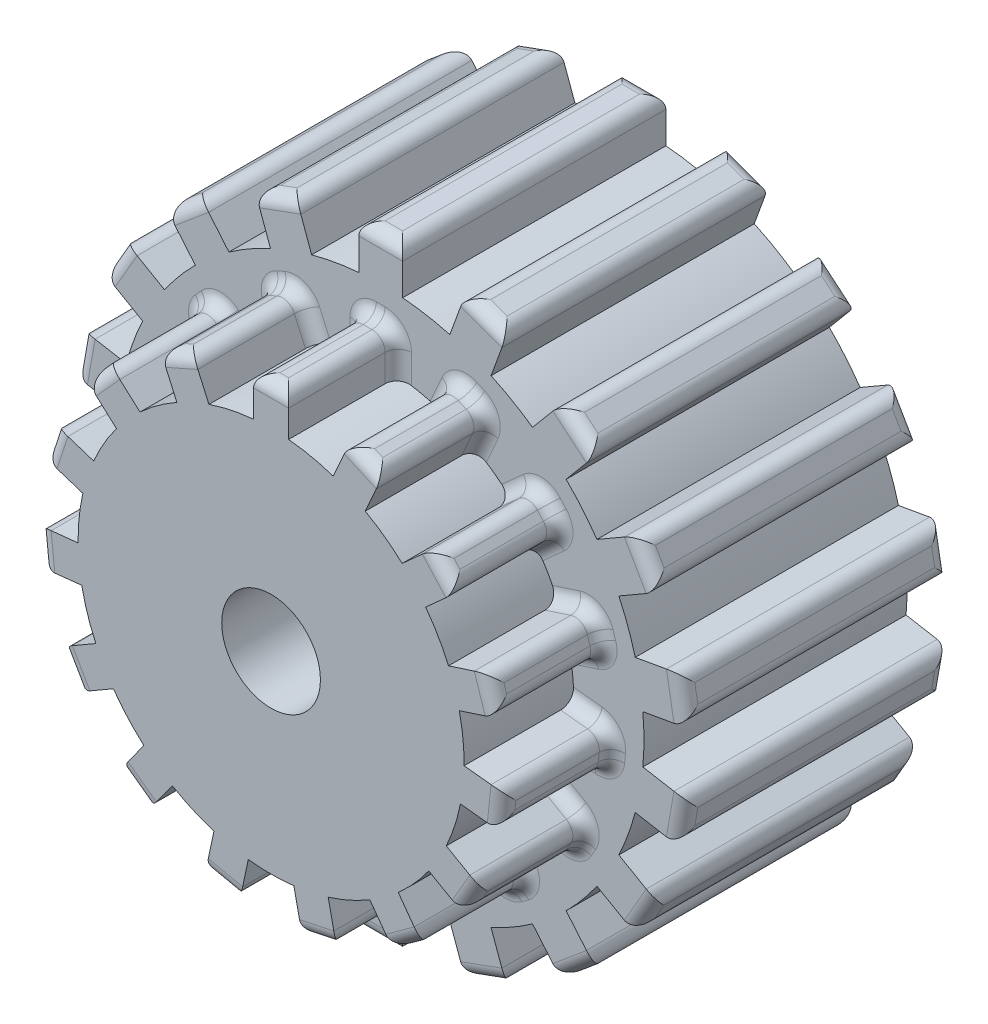
SolidWorks part; units mm, degrees
ref_plane "Front Plane" through (0, 0, 0) normal (0, 0, 1) x (1, 0, 0)
ref_plane "Top Plane" through (0, 0, 0) normal (0, 1, 0) x (1, 0, 0)
ref_plane "Right Plane" through (0, 0, 0) normal (1, 0, 0) x (0, 0, -1)
sketch "Sketch2" plane through (0, 0, 0) normal (0, 0, 1) x (1, 0, 0)
  circle A0 centre (0, 0) radius 60
extrude "Boss-Extrude1" add sketch "Sketch2" along normal blind 60
sketch "Sketch3" plane through (0, 0, 60) normal (0, 0, 1) x (1, 0, 0)
  line L0 (0, 60) -> (0, 70) construction
  line L1 (5, 70) -> (-5, 70)
  line L2 (-5, 70) -> (-5, 59.5215)
  line L3 (-5, 59.5215) -> (5, 59.5215)
  line L4 (5, 59.5215) -> (5, 70)
  circle A0 centre (0, 0) radius 60 construction
  point P9 (0, 70)
extrude "Boss-Extrude2" add sketch "Sketch3" against normal blind 60
fillet "Fillet2" radius 3 4 edges at (-5, 70, 30) (0, 70, 60) (0, 70, 0) (5, 70, 30)
pattern_circular "CirPattern1" count 18 over 360 about axis through (0, 0, 0) along (0, 0, 1) of "Fillet2", "Boss-Extrude2"
sketch "Sketch4" plane through (0, 0, 60) normal (0, 0, 1) x (1, 0, 0)
  circle A0 centre (0, 0) radius 10
extrude "Cut-Extrude1" cut sketch "Sketch4" against normal blind 60
sketch "Sketch5" plane through (0, 0, 60) normal (0, 0, 1) x (1, 0, 0)
  circle A0 centre (0, 0) radius 44
extrude "Boss-Extrude3" add sketch "Sketch5" along normal blind 25
sketch "Sketch6" plane through (0, 0, 85) normal (0, 0, 1) x (1, 0, 0)
  line L0 (0, 44) -> (0, 53) construction
  line L1 (4, 53) -> (-4, 53)
  line L2 (-4, 53) -> (-4, 42.9556)
  line L3 (-4, 42.9556) -> (4, 42.9556)
  line L4 (4, 42.9556) -> (4, 53)
  circle A0 centre (0, 0) radius 44 construction
  circle A1 centre (0, 0) radius 44 construction
  point P10 (0, 53)
extrude "Boss-Extrude4" add sketch "Sketch6" against normal blind 25
sketch "Sketch7" plane through (0, 0, 0) normal (0, 0, -1) x (-1, 0, 0)
  circle A0 centre (0, 0) radius 10
extrude "Cut-Extrude2" cut sketch "Sketch7" against normal blind 90
fillet "Fillet3" radius 3 6 edges at (-4, 48.4089, 60) (4, 48.4089, 60) (-4, 53, 72.5) (0, 53, 85) (0, 53, 60) (4, 53, 72.5)
pattern_circular "CirPattern2" count 15 over 360 about axis through (0, 0, 0) along (0, 0, 1) of "Boss-Extrude4", "Fillet3"
sketch "Sketch8" plane through (0, 0, 0) normal (0, 0, -1) x (-1, 0, 0)
  circle A0 centre (0, 0) radius 11.25
extrude "Cut-Extrude3" cut sketch "Sketch8" against normal up to surface (85 mm away) up to face at (0, 0, 85)
